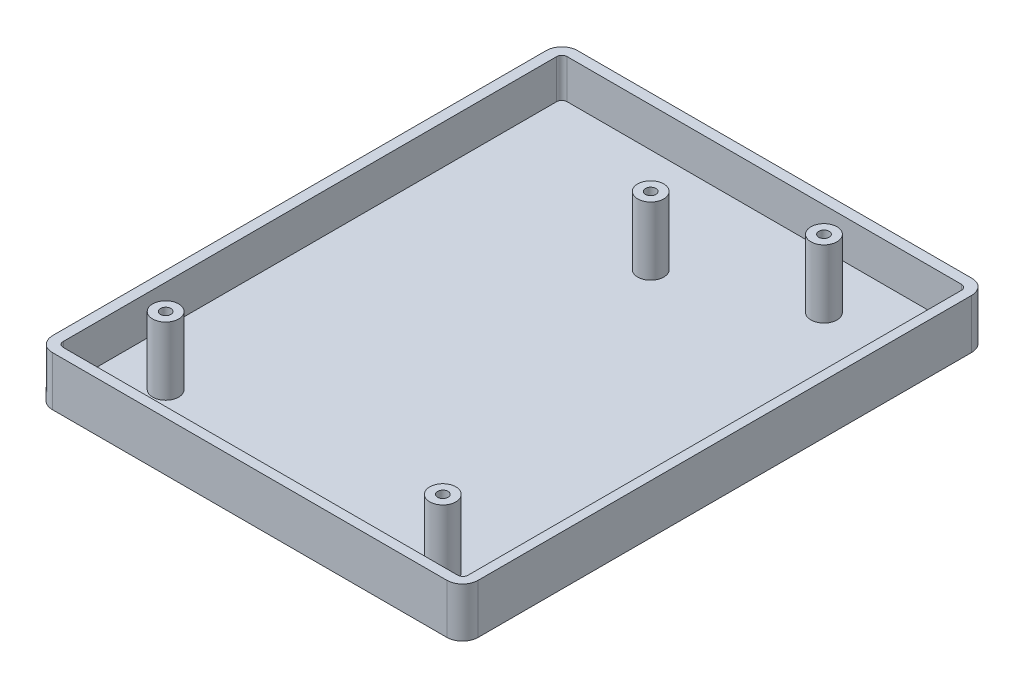
SolidWorks part; units mm, degrees
ref_plane "Front Plane" through (0, 0, 0) normal (0, 0, 1) x (1, 0, 0)
ref_plane "Top Plane" through (0, 0, 0) normal (0, 1, 0) x (1, 0, 0)
ref_plane "Right Plane" through (0, 0, 0) normal (1, 0, 0) x (0, 0, -1)
sketch "Sketch1" plane through (0, 0, 0) normal (0, 1, 0) x (1, 0, 0)
  line L0 (0.8584, 97.0707) -> (76.5584, 97.0707)
  line L1 (77.5584, 96.0707) -> (77.5584, 1.3707)
  line L2 (76.5584, 0.3707) -> (0.8584, 0.3707)
  line L3 (-0.1416, 1.3707) -> (-0.1416, 96.0707)
  line L4 (0.8584, 99.0707) -> (76.5584, 99.0707)
  line L5 (79.5584, 96.0707) -> (79.5584, 1.3707)
  line L6 (76.5584, -1.6293) -> (0.8584, -1.6293)
  line L7 (-2.1416, 1.3707) -> (-2.1416, 96.0707)
  arc A0 (76.5584, 97.0707) -> (77.5584, 96.0707) centre (76.5584, 96.0707) cw
  arc A1 (77.5584, 1.3707) -> (76.5584, 0.3707) centre (76.5584, 1.3707) cw
  arc A2 (0.8584, 0.3707) -> (-0.1416, 1.3707) centre (0.8584, 1.3707) cw
  arc A3 (-0.1416, 96.0707) -> (0.8584, 97.0707) centre (0.8584, 96.0707) cw
  arc A4 (76.5584, 99.0707) -> (79.5584, 96.0707) centre (76.5584, 96.0707) cw
  arc A5 (79.5584, 1.3707) -> (76.5584, -1.6293) centre (76.5584, 1.3707) cw
  arc A6 (0.8584, -1.6293) -> (-2.1416, 1.3707) centre (0.8584, 1.3707) cw
  arc A7 (-2.1416, 96.0707) -> (0.8584, 99.0707) centre (0.8584, 96.0707) cw
  line B0 (55.3084, 41.6207) -> (55.3084, 55.5207)
  line B1 (17.3084, 79.6207) -> (17.3084, 93.5207)
  line B2 (17.3084, 93.5207) -> (3.4084, 93.5207)
  line B3 (0.8584, 97.0707) -> (76.5584, 97.0707)
  line B4 (74.3084, 93.5207) -> (60.4084, 93.5207)
  line B5 (77.5584, 96.0707) -> (77.5584, 1.3707)
  arc B6 (77.5584, 96.0707) -> (76.5584, 97.0707) centre (76.5584, 96.0707) ccw
  arc B7 (76.5584, 0.3707) -> (77.5584, 1.3707) centre (76.5584, 1.3707) ccw
  line B8 (76.5584, 0.3707) -> (0.8584, 0.3707)
  arc B9 (-0.1416, 1.3707) -> (0.8584, 0.3707) centre (0.8584, 1.3707) ccw
  line B10 (-0.1416, 1.3707) -> (-0.1416, 96.0707)
  line B11 (22.4084, 93.5207) -> (22.4084, 79.6207)
  arc B12 (0.8584, 97.0707) -> (-0.1416, 96.0707) centre (0.8584, 96.0707) ccw
  line B13 (3.4084, 55.5207) -> (3.4084, 41.6207)
  line B14 (12.9084, 3.6207) -> (26.8084, 3.6207)
  line B15 (26.8084, 3.6207) -> (26.8084, 17.5207)
  line B16 (26.8084, 17.5207) -> (12.9084, 17.5207)
  line B17 (12.9084, 17.5207) -> (12.9084, 3.6207)
  line B18 (3.4084, 22.6207) -> (17.3084, 22.6207)
  line B19 (17.3084, 22.6207) -> (17.3084, 36.5207)
  line B20 (17.3084, 36.5207) -> (3.4084, 36.5207)
  line B21 (3.4084, 36.5207) -> (3.4084, 22.6207)
  line B22 (3.4084, 41.6207) -> (17.3084, 41.6207)
  line B23 (17.3084, 41.6207) -> (17.3084, 55.5207)
  line B24 (17.3084, 55.5207) -> (3.4084, 55.5207)
  line B25 (3.4084, 60.6207) -> (17.3084, 60.6207)
  line B26 (17.3084, 60.6207) -> (17.3084, 74.5207)
  line B27 (17.3084, 74.5207) -> (3.4084, 74.5207)
  line B28 (3.4084, 74.5207) -> (3.4084, 60.6207)
  line B29 (3.4084, 79.6207) -> (17.3084, 79.6207)
  line B30 (3.4084, 93.5207) -> (3.4084, 79.6207)
  line B31 (22.4084, 22.6207) -> (36.3084, 22.6207)
  line B32 (36.3084, 22.6207) -> (36.3084, 36.5207)
  line B33 (36.3084, 36.5207) -> (22.4084, 36.5207)
  line B34 (22.4084, 36.5207) -> (22.4084, 22.6207)
  line B35 (22.4084, 41.6207) -> (36.3084, 41.6207)
  line B36 (36.3084, 41.6207) -> (36.3084, 55.5207)
  line B37 (36.3084, 55.5207) -> (22.4084, 55.5207)
  line B38 (22.4084, 55.5207) -> (22.4084, 41.6207)
  line B39 (22.4084, 60.6207) -> (36.3084, 60.6207)
  line B40 (36.3084, 60.6207) -> (36.3084, 74.5207)
  line B41 (36.3084, 74.5207) -> (22.4084, 74.5207)
  line B42 (22.4084, 74.5207) -> (22.4084, 60.6207)
  line B43 (22.4084, 79.6207) -> (36.3084, 79.6207)
  line B44 (36.3084, 79.6207) -> (36.3084, 93.5207)
  line B45 (36.3084, 93.5207) -> (22.4084, 93.5207)
  line B46 (41.4084, 3.6207) -> (55.3084, 3.6207)
  line B47 (55.3084, 3.6207) -> (55.3084, 17.5207)
  line B48 (55.3084, 17.5207) -> (41.4084, 17.5207)
  line B49 (41.4084, 17.5207) -> (41.4084, 3.6207)
  line B50 (41.4084, 22.6207) -> (55.3084, 22.6207)
  line B51 (55.3084, 22.6207) -> (55.3084, 36.5207)
  line B52 (55.3084, 36.5207) -> (41.4084, 36.5207)
  line B53 (41.4084, 36.5207) -> (41.4084, 22.6207)
  line B54 (41.4084, 41.6207) -> (55.3084, 41.6207)
  line B55 (55.3084, 55.5207) -> (41.4084, 55.5207)
  line B56 (41.4084, 55.5207) -> (41.4084, 41.6207)
  line B57 (41.4084, 60.6207) -> (55.3084, 60.6207)
  line B58 (55.3084, 60.6207) -> (55.3084, 74.5207)
  line B59 (55.3084, 74.5207) -> (41.4084, 74.5207)
  line B60 (41.4084, 74.5207) -> (41.4084, 60.6207)
  line B61 (41.4084, 79.6207) -> (55.3084, 79.6207)
  line B62 (55.3084, 79.6207) -> (55.3084, 93.5207)
  line B63 (55.3084, 93.5207) -> (41.4084, 93.5207)
  line B64 (41.4084, 93.5207) -> (41.4084, 79.6207)
  line B65 (60.4084, 13.1207) -> (74.3084, 13.1207)
  line B66 (74.3084, 13.1207) -> (74.3084, 27.0207)
  line B67 (74.3084, 27.0207) -> (60.4084, 27.0207)
  line B68 (60.4084, 27.0207) -> (60.4084, 13.1207)
  line B69 (60.4084, 51.1207) -> (74.3084, 51.1207)
  line B70 (74.3084, 51.1207) -> (74.3084, 65.0207)
  line B71 (74.3084, 65.0207) -> (60.4084, 65.0207)
  line B72 (60.4084, 65.0207) -> (60.4084, 51.1207)
  line B73 (60.4084, 79.6207) -> (74.3084, 79.6207)
  line B74 (74.3084, 79.6207) -> (74.3084, 93.5207)
  line B75 (60.4084, 93.5207) -> (60.4084, 79.6207)
sketch_block_instance "Block1-1"
sketch_block "Block1"
extrude "Boss-Extrude1" add sketch "Sketch1" along normal blind 2 contours A3 L3 A2 L2 A1 L1 A0 L0 B75 B4 B74 B73 B72 B71 B70 B69 B68 B67 B66 B65 B64 B63 B62 B61 B60 B59 B58 B57 B56 B55 B0 B54 B53 B52 B51 B50 B49 B48 B47 B46 B11 B45 | B33 B34 B31 B32 | B16 B17 B14 B15 | B20 B21 B18 B19 | B37 B38 B35 B36 | B24 B13 B22 B23 | B27 B28 B25 B26 | B41 B42 B39 B40 | B45 B11 B43 B44 | B2 B30 B29 B1 | B63 B64 B61 B62 | B59 B60 B57 B58 | B55 B56 B54 B0 | B52 B53 B50 B51 | B48 B49 B46 B47 | B67 B68 B65 B66 | B71 B72 B69 B70 | B4 B75 B73 B74 | A7 L7 A6 L6 A5 L5 A4 L4 L3 A3 L0 A0 L1 A1 L2 A2
sketch "Sketch2" plane through (0, 2, 0) normal (0, 1, 0) x (1, 0, 0)
  circle B0 centre (36.9813, 77.0708) radius 1
  circle B1 centre (36.9813, 77.0708) radius 2.5
  line B2 (-1.6187, 1.3708) -> (-1.6187, 96.0708)
  line B3 (0.8813, 98.5708) -> (76.5813, 98.5708)
  line B4 (79.0813, 96.0708) -> (79.0813, 1.3708)
  line B5 (76.5813, -1.1292) -> (0.8813, -1.1292)
  arc B6 (0.8813, 98.5708) -> (-1.6187, 96.0708) centre (0.8813, 96.0708) ccw
  arc B7 (79.0813, 96.0708) -> (76.5813, 98.5708) centre (76.5813, 96.0708) ccw
  arc B8 (76.5813, -1.1292) -> (79.0813, 1.3708) centre (76.5813, 1.3708) ccw
  arc B9 (-1.6187, 1.3708) -> (0.8813, -1.1292) centre (0.8813, 1.3708) ccw
  circle B10 centre (10.3813, 10.5708) radius 2.5
  circle B11 centre (60.7313, 86.5708) radius 2.5
  circle B12 centre (67.3813, 6.7708) radius 2.5
  circle B13 centre (10.3813, 10.5708) radius 1
  circle B14 centre (60.7313, 86.5708) radius 1
  circle B15 centre (67.3813, 6.7708) radius 1
sketch_block_instance "boardwithholes-1"
sketch_block "boardwithholes"
extrude "Boss-Extrude2" add sketch "Sketch2" along normal blind 13 contours B10 B13 | B12 B15 | B11 B14 | B1 B0
sketch "Sketch3" plane through (0, 2, 0) normal (0, 1, 0) x (1, 0, 0)
  line L0 (1.0442, 96.9561) -> (76.7442, 96.9561)
  line L1 (77.7442, 95.9561) -> (77.7442, 1.2561)
  line L2 (76.7442, 0.2561) -> (1.0442, 0.2561)
  line L3 (0.0442, 1.2561) -> (0.0442, 95.9561)
  line L4 (1.0442, 98.9561) -> (76.7442, 98.9561)
  line L5 (79.7442, 95.9561) -> (79.7442, 1.2561)
  line L6 (76.7442, -1.7439) -> (1.0442, -1.7439)
  line L7 (-1.9558, 1.2561) -> (-1.9558, 95.9561)
  arc A0 (76.7442, 96.9561) -> (77.7442, 95.9561) centre (76.7442, 95.9561) cw
  arc A1 (77.7442, 1.2561) -> (76.7442, 0.2561) centre (76.7442, 1.2561) cw
  arc A2 (1.0442, 0.2561) -> (0.0442, 1.2561) centre (1.0442, 1.2561) cw
  arc A3 (0.0442, 95.9561) -> (1.0442, 96.9561) centre (1.0442, 95.9561) cw
  arc A4 (76.7442, 98.9561) -> (79.7442, 95.9561) centre (76.7442, 95.9561) cw
  arc A5 (79.7442, 1.2561) -> (76.7442, -1.7439) centre (76.7442, 1.2561) cw
  arc A6 (1.0442, -1.7439) -> (-1.9558, 1.2561) centre (1.0442, 1.2561) cw
  arc A7 (-1.9558, 95.9561) -> (1.0442, 98.9561) centre (1.0442, 95.9561) cw
  line B0 (55.4942, 41.5061) -> (55.4942, 55.4061)
  line B1 (17.4942, 79.5061) -> (17.4942, 93.4061)
  line B2 (17.4942, 93.4061) -> (3.5942, 93.4061)
  line B3 (1.0442, 96.9561) -> (76.7442, 96.9561)
  line B4 (74.4942, 93.4061) -> (60.5942, 93.4061)
  line B5 (77.7442, 95.9561) -> (77.7442, 1.2561)
  arc B6 (77.7442, 95.9561) -> (76.7442, 96.9561) centre (76.7442, 95.9561) ccw
  arc B7 (76.7442, 0.2561) -> (77.7442, 1.2561) centre (76.7442, 1.2561) ccw
  line B8 (76.7442, 0.2561) -> (1.0442, 0.2561)
  arc B9 (0.0442, 1.2561) -> (1.0442, 0.2561) centre (1.0442, 1.2561) ccw
  line B10 (0.0442, 1.2561) -> (0.0442, 95.9561)
  line B11 (22.5942, 93.4061) -> (22.5942, 79.5061)
  arc B12 (1.0442, 96.9561) -> (0.0442, 95.9561) centre (1.0442, 95.9561) ccw
  line B13 (3.5942, 55.4061) -> (3.5942, 41.5061)
  line B14 (13.0942, 3.5061) -> (26.9942, 3.5061)
  line B15 (26.9942, 3.5061) -> (26.9942, 17.4061)
  line B16 (26.9942, 17.4061) -> (13.0942, 17.4061)
  line B17 (13.0942, 17.4061) -> (13.0942, 3.5061)
  line B18 (3.5942, 22.5061) -> (17.4942, 22.5061)
  line B19 (17.4942, 22.5061) -> (17.4942, 36.4061)
  line B20 (17.4942, 36.4061) -> (3.5942, 36.4061)
  line B21 (3.5942, 36.4061) -> (3.5942, 22.5061)
  line B22 (3.5942, 41.5061) -> (17.4942, 41.5061)
  line B23 (17.4942, 41.5061) -> (17.4942, 55.4061)
  line B24 (17.4942, 55.4061) -> (3.5942, 55.4061)
  line B25 (3.5942, 60.5061) -> (17.4942, 60.5061)
  line B26 (17.4942, 60.5061) -> (17.4942, 74.4061)
  line B27 (17.4942, 74.4061) -> (3.5942, 74.4061)
  line B28 (3.5942, 74.4061) -> (3.5942, 60.5061)
  line B29 (3.5942, 79.5061) -> (17.4942, 79.5061)
  line B30 (3.5942, 93.4061) -> (3.5942, 79.5061)
  line B31 (22.5942, 22.5061) -> (36.4942, 22.5061)
  line B32 (36.4942, 22.5061) -> (36.4942, 36.4061)
  line B33 (36.4942, 36.4061) -> (22.5942, 36.4061)
  line B34 (22.5942, 36.4061) -> (22.5942, 22.5061)
  line B35 (22.5942, 41.5061) -> (36.4942, 41.5061)
  line B36 (36.4942, 41.5061) -> (36.4942, 55.4061)
  line B37 (36.4942, 55.4061) -> (22.5942, 55.4061)
  line B38 (22.5942, 55.4061) -> (22.5942, 41.5061)
  line B39 (22.5942, 60.5061) -> (36.4942, 60.5061)
  line B40 (36.4942, 60.5061) -> (36.4942, 74.4061)
  line B41 (36.4942, 74.4061) -> (22.5942, 74.4061)
  line B42 (22.5942, 74.4061) -> (22.5942, 60.5061)
  line B43 (22.5942, 79.5061) -> (36.4942, 79.5061)
  line B44 (36.4942, 79.5061) -> (36.4942, 93.4061)
  line B45 (36.4942, 93.4061) -> (22.5942, 93.4061)
  line B46 (41.5942, 3.5061) -> (55.4942, 3.5061)
  line B47 (55.4942, 3.5061) -> (55.4942, 17.4061)
  line B48 (55.4942, 17.4061) -> (41.5942, 17.4061)
  line B49 (41.5942, 17.4061) -> (41.5942, 3.5061)
  line B50 (41.5942, 22.5061) -> (55.4942, 22.5061)
  line B51 (55.4942, 22.5061) -> (55.4942, 36.4061)
  line B52 (55.4942, 36.4061) -> (41.5942, 36.4061)
  line B53 (41.5942, 36.4061) -> (41.5942, 22.5061)
  line B54 (41.5942, 41.5061) -> (55.4942, 41.5061)
  line B55 (55.4942, 55.4061) -> (41.5942, 55.4061)
  line B56 (41.5942, 55.4061) -> (41.5942, 41.5061)
  line B57 (41.5942, 60.5061) -> (55.4942, 60.5061)
  line B58 (55.4942, 60.5061) -> (55.4942, 74.4061)
  line B59 (55.4942, 74.4061) -> (41.5942, 74.4061)
  line B60 (41.5942, 74.4061) -> (41.5942, 60.5061)
  line B61 (41.5942, 79.5061) -> (55.4942, 79.5061)
  line B62 (55.4942, 79.5061) -> (55.4942, 93.4061)
  line B63 (55.4942, 93.4061) -> (41.5942, 93.4061)
  line B64 (41.5942, 93.4061) -> (41.5942, 79.5061)
  line B65 (60.5942, 13.0061) -> (74.4942, 13.0061)
  line B66 (74.4942, 13.0061) -> (74.4942, 26.9061)
  line B67 (74.4942, 26.9061) -> (60.5942, 26.9061)
  line B68 (60.5942, 26.9061) -> (60.5942, 13.0061)
  line B69 (60.5942, 51.0061) -> (74.4942, 51.0061)
  line B70 (74.4942, 51.0061) -> (74.4942, 64.9061)
  line B71 (74.4942, 64.9061) -> (60.5942, 64.9061)
  line B72 (60.5942, 64.9061) -> (60.5942, 51.0061)
  line B73 (60.5942, 79.5061) -> (74.4942, 79.5061)
  line B74 (74.4942, 79.5061) -> (74.4942, 93.4061)
  line B75 (60.5942, 93.4061) -> (60.5942, 79.5061)
  arc M23 (-2.1416, 1.3707) -> (0.8584, -1.6293) centre (0.8584, 1.3707) ccw
  line M24 (0.8584, -1.6293) -> (76.5584, -1.6293)
  arc M25 (76.5584, -1.6293) -> (79.5584, 1.3707) centre (76.5584, 1.3707) ccw
  line M26 (79.5584, 1.3707) -> (79.5584, 96.0707)
  arc M27 (79.5584, 96.0707) -> (76.5584, 99.0707) centre (76.5584, 96.0707) ccw
sketch_block_instance "Block1-2"
extrude "Boss-Extrude3" add sketch "Sketch3" along normal blind 7.5 contours A7 L7 A6 A4 L4 L3 A3 L0 A0 L1 A1 L2 A2 M23 M24 M25 M26 M27
